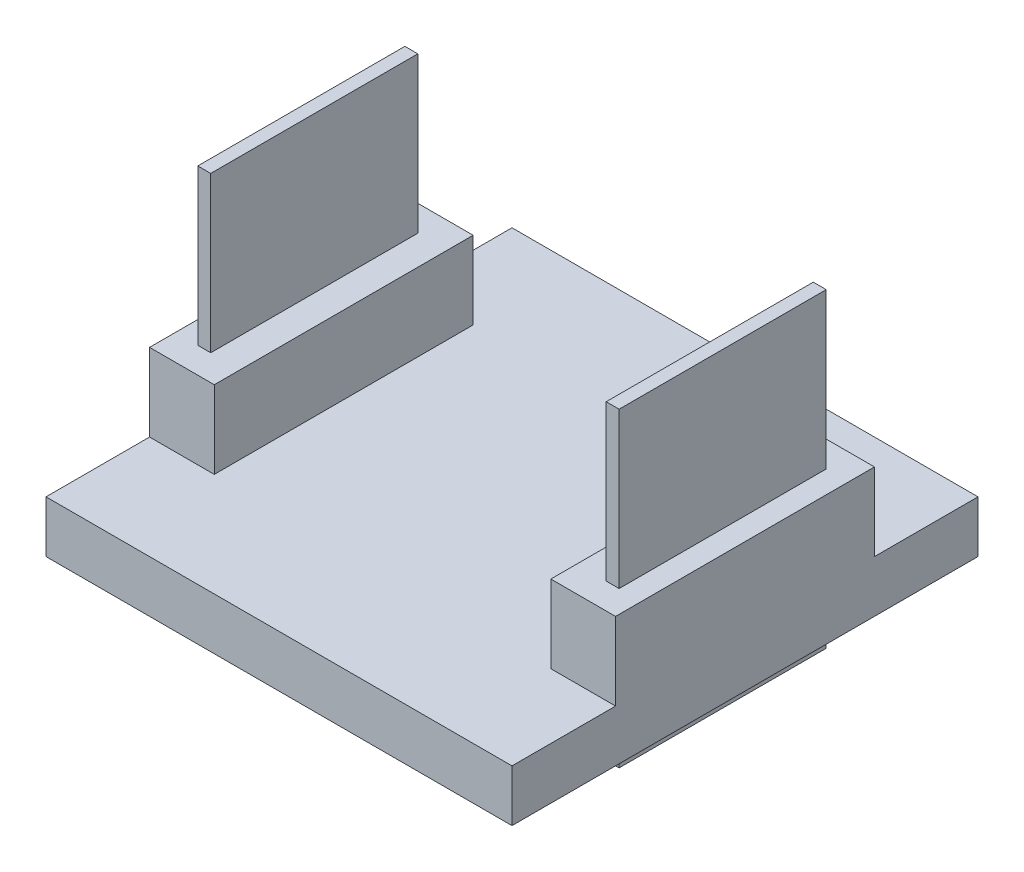
SolidWorks part; units mm, degrees
ref_plane "Front Plane" through (0, 0, 0) normal (0, 0, 1) x (1, 0, 0)
ref_plane "Top Plane" through (0, 0, 0) normal (0, 1, 0) x (1, 0, 0)
ref_plane "Right Plane" through (0, 0, 0) normal (1, 0, 0) x (0, 0, -1)
sketch "Sketch1" plane through (0, 0, 0) normal (0, 1, 0) x (1, 0, 0)
  line L1 (-9, -9) -> (9, -9)
  line L2 (-9, -9) -> (-9, 9)
  line L3 (-9, 9) -> (9, 9)
  line L4 (9, -9) -> (9, 9)
  line L5 (-9, -9) -> (9, 9) construction
  line L6 (-9, 9) -> (9, -9) construction
  point P0 (0, 0)
  dimension "D1" = 18
  dimension "D2" = 18
extrude "Boss-Extrude1" add sketch "Sketch1" along normal blind 2
sketch "Sketch2" plane through (0, 2, 0) normal (0, 1, 0) x (1, 0, 0)
  line L0 (0, 9) -> (0, -9) construction
  line L1 (9, 9) -> (-9, 9) construction
  line L2 (-9, -9) -> (9, -9) construction
  line L3 (-9, 9) -> (-9, -9) construction
  line L4 (-9, -5) -> (-6.5, -5)
  line L5 (-9, -5) -> (-9, 5)
  line L6 (-9, 5) -> (-6.5, 5)
  line L7 (-6.5, -5) -> (-6.5, 5)
  line L8 (9, 0) -> (-9, 0) construction
  line L9 (9, -9) -> (9, 9) construction
  line L10 (9, 5) -> (6.5, 5)
  line L11 (6.5, -5) -> (6.5, 5)
  line L12 (9, -5) -> (6.5, -5)
  line L13 (9, -5) -> (9, 5)
  point P17 (-9, 0)
  dimension "D1" = 2.5
  dimension "D2" = 10
extrude "Boss-Extrude2" add sketch "Sketch2" along normal blind 3
sketch "Sketch3" plane through (0, 5, 0) normal (0, 1, 0) x (1, 0, 0)
  line L0 (0, 9) -> (0, -9) construction
  line L1 (-8.1376, -4) -> (-7.6376, -4)
  line L2 (-8.1376, -4) -> (-8.1376, 4)
  line L3 (-8.1376, 4) -> (-7.6376, 4)
  line L4 (-7.6376, -4) -> (-7.6376, 4)
  line L5 (-8.1376, -4) -> (-7.6376, 4) construction
  line L6 (-8.1376, 4) -> (-7.6376, -4) construction
  line L7 (9, 9) -> (-9, 9) construction
  line L8 (-9, -9) -> (9, -9) construction
  line L9 (9, 0) -> (-9, 0) construction
  line L10 (9, -5) -> (9, 5) construction
  line L11 (-9, 5) -> (-9, -5) construction
  line L12 (8.1376, 4) -> (7.6376, 4)
  line L13 (7.6376, -4) -> (7.6376, 4)
  line L14 (8.1376, -4) -> (7.6376, -4)
  line L15 (8.1376, -4) -> (8.1376, 4)
  point P0 (-7.8876, 0)
  dimension "D1" = 0.5
  dimension "D2" = 8
extrude "Boss-Extrude3" add sketch "Sketch3" along normal blind 6 and the other way blind 6
